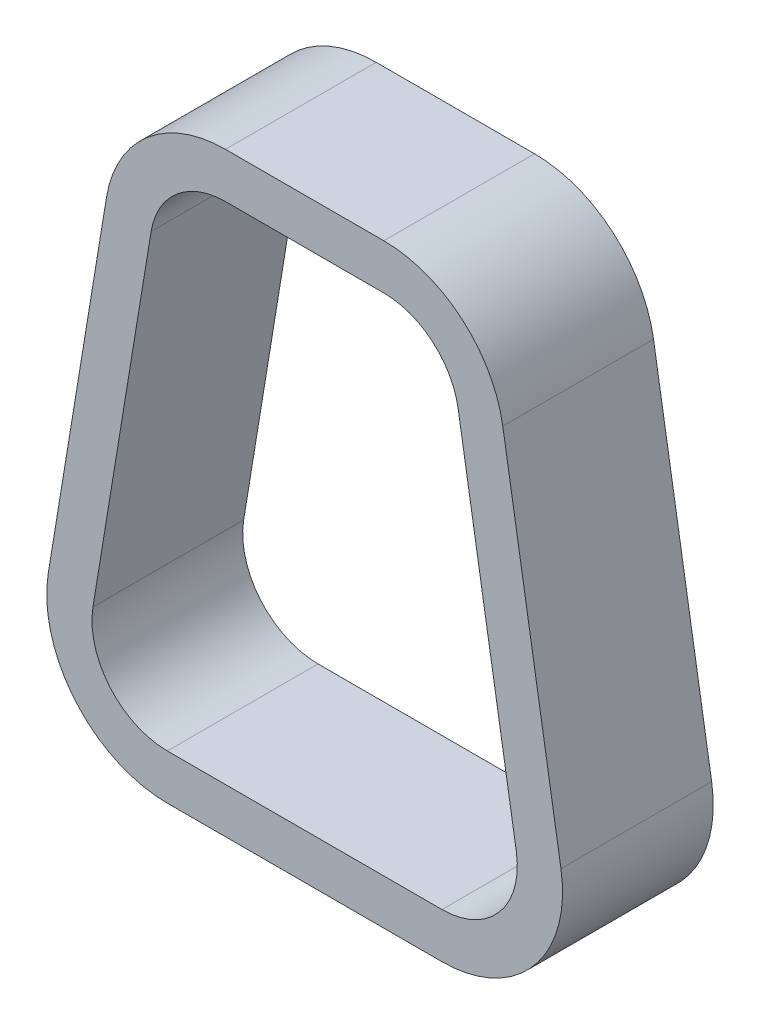
SolidWorks part; units mm, degrees
ref_plane "Plan de face" through (0, 0, 0) normal (0, 0, 1) x (1, 0, 0)
ref_plane "Plan de dessus" through (0, 0, 0) normal (0, 1, 0) x (1, 0, 0)
ref_plane "Plan de droite" through (0, 0, 0) normal (1, 0, 0) x (0, 0, -1)
sketch "Esquisse1" plane through (0, 0, 0) normal (0, 0, 1) x (1, 0, 0)
  line L4 (0, 0) -> (0, 124.6654) construction
  line L5 (-15, 0) -> (15, 0)
  line L6 (-9.5, 33.5) -> (9.5, 33.5)
  line L7 (9.5, 33.5) -> (15, 0)
  line L8 (-9.5, 33.5) -> (-15, 0)
  point P9 (0, 33.5)
  dimension "D1" = 15
  dimension "D2" = 9.5
  dimension "D3" = 33.5
extrude "Boss.-Extru.2" add sketch "Esquisse1" along normal blind 10
fillet "Congé2" radius 5 4 edges at (-15, 0, 5) (15, 0, 5) (9.5, 33.5, 5) (-9.5, 33.5, 5)
shell "Coque3" thickness 3
